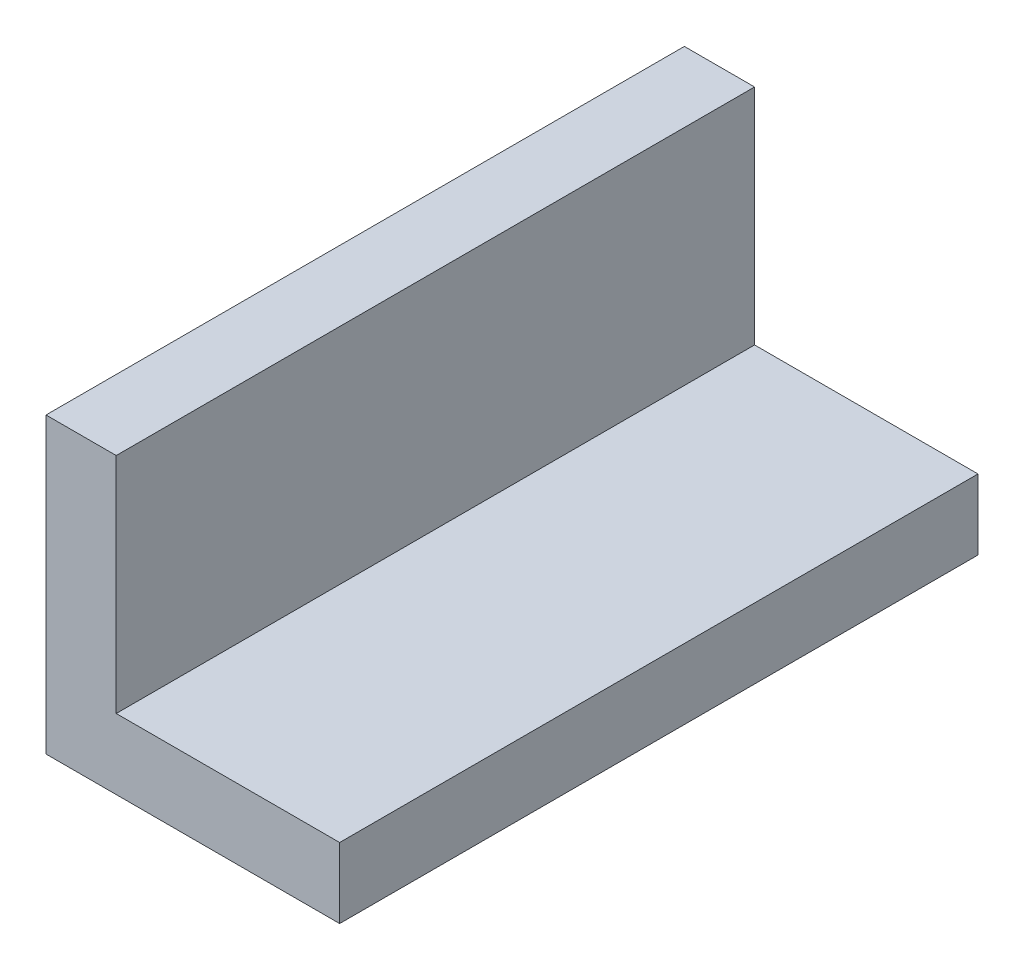
SolidWorks part; units mm, degrees
ref_plane "Plan de face" through (0, 0, 0) normal (0, 0, 1) x (1, 0, 0)
ref_plane "Plan de dessus" through (0, 0, 0) normal (0, 1, 0) x (1, 0, 0)
ref_plane "Plan de droite" through (0, 0, 0) normal (1, 0, 0) x (0, 0, -1)
sketch "Esquisse1" plane through (0, 0, 0) normal (0, 0, 1) x (1, 0, 0)
  line L0 (11, 0) -> (11, 70)
  line L1 (11, 70) -> (-11, 70)
  line L2 (-11, 70) -> (-11, -22)
  line L3 (-11, -22) -> (81, -22)
  line L4 (81, -22) -> (81, 0)
  line L5 (81, 0) -> (11, 0)
  line L6 (11, 0) -> (0, 0) construction
  line L7 (0, 0) -> (-11, 0) construction
  point P8 (8.5, 0)
  dimension "D1" = 22
  dimension "D2" = 70
  dimension "D3" = 70
extrude "Boss.-Extru.1" add sketch "Esquisse1" along normal mid plane 200
